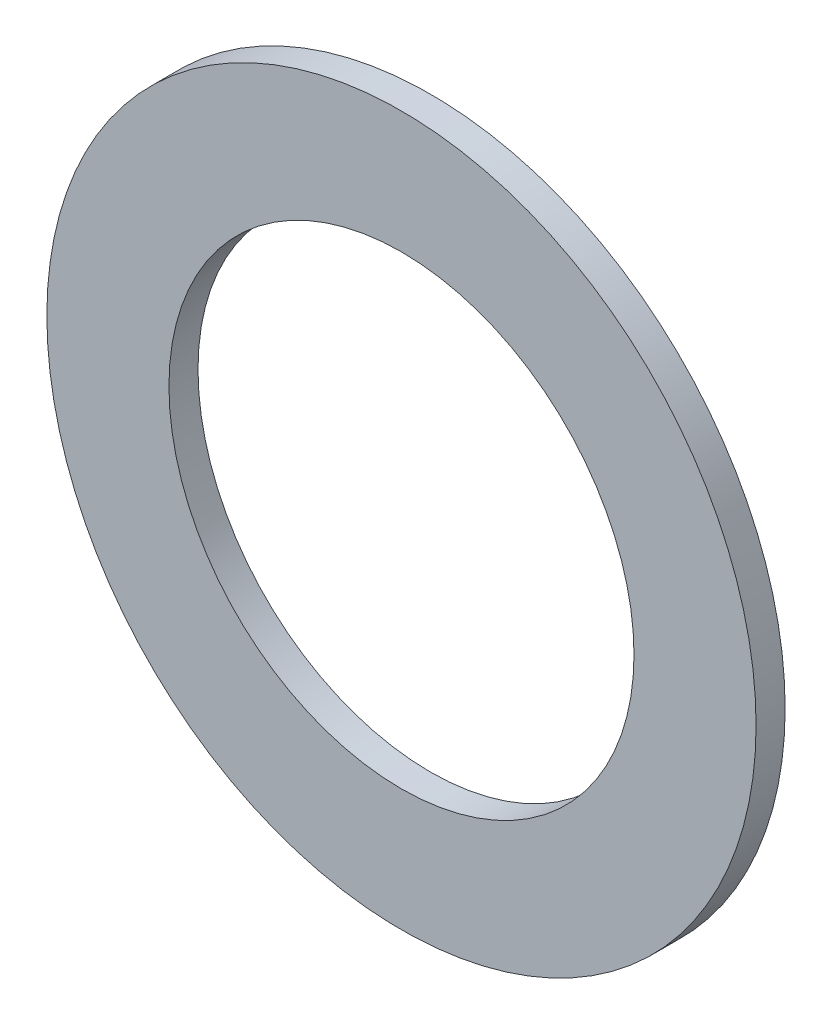
SolidWorks part; units mm, degrees
material "铸造合金钢"
ref_plane "前视基准面" through (0, 0, 0) normal (0, 0, 1) x (1, 0, 0)
ref_plane "上视基准面" through (0, 0, 0) normal (0, 1, 0) x (1, 0, 0)
ref_plane "右视基准面" through (0, 0, 0) normal (1, 0, 0) x (0, 0, -1)
sketch "草图1" plane through (0, 0, 0) normal (0, 0, 1) x (1, 0, 0)
  circle A0 centre (0, 0) radius 8
  circle A1 centre (0, 0) radius 12.2
extrude "凸台-拉伸1" add sketch "草图1" along normal blind 1
